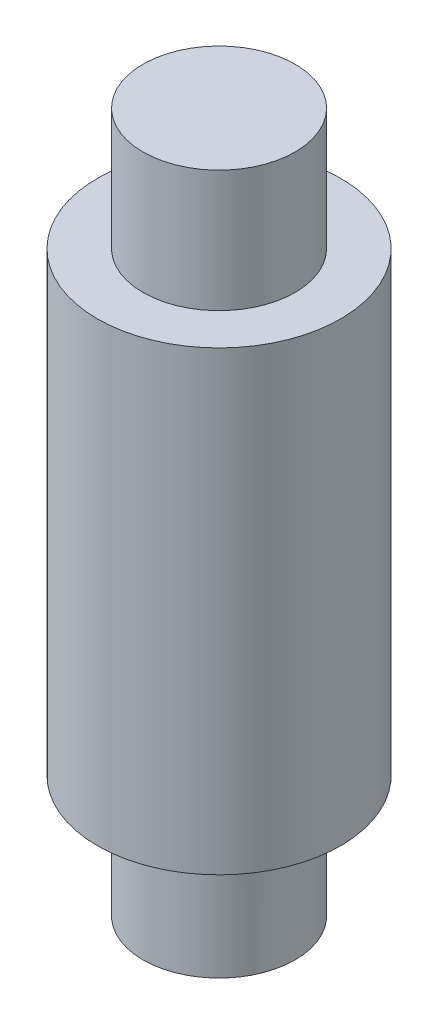
SolidWorks part; units mm, degrees
ref_plane "前视基准面" through (0, 0, 0) normal (0, 0, 1) x (1, 0, 0)
ref_plane "上视基准面" through (0, 0, 0) normal (0, 1, 0) x (1, 0, 0)
ref_plane "右视基准面" through (0, 0, 0) normal (1, 0, 0) x (0, 0, -1)
sketch "草图1" plane through (0, 0, 0) normal (0, 1, 0) x (1, 0, 0)
  circle A0 centre (0, 0) radius 4
  dimension "D1" = 8
extrude "凸台-拉伸1" add sketch "草图1" along normal blind 15
sketch "草图2" plane through (0, 15, 0) normal (0, 1, 0) x (1, 0, 0)
  circle A0 centre (0, 0) radius 2.5
  dimension "D1" = 5
extrude "凸台-拉伸2" add sketch "草图2" along normal blind 4
sketch "草图3" plane through (0, 0, 0) normal (0, -1, 0) x (-1, 0, 0)
  circle A0 centre (0, 0) radius 2.5
  dimension "D1" = 5
extrude "凸台-拉伸3" add sketch "草图3" along normal blind 4
